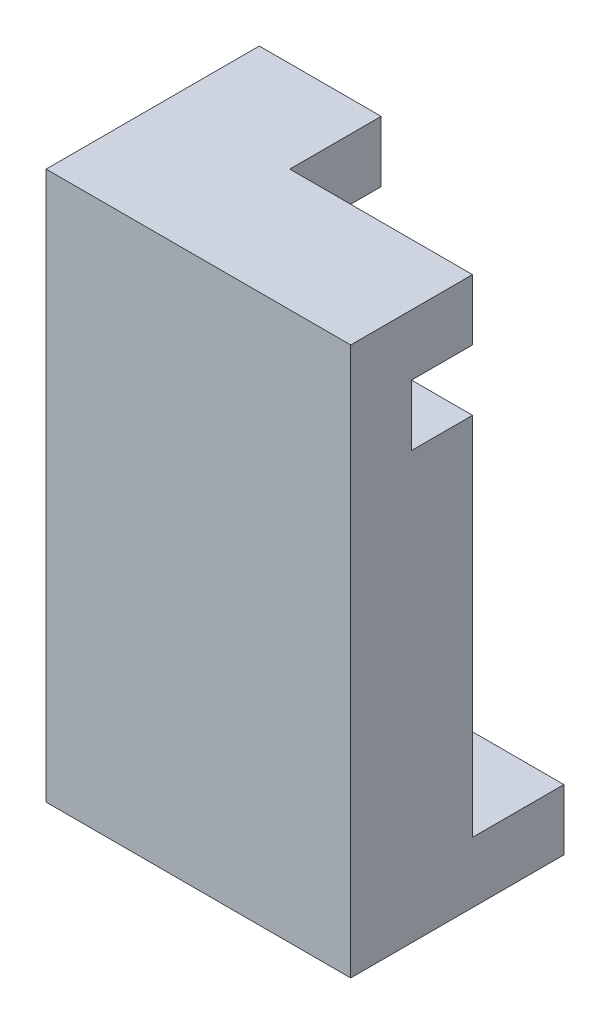
SolidWorks part; units mm, degrees
ref_plane "정면" through (0, 0, 0) normal (0, 0, 1) x (1, 0, 0)
ref_plane "윗면" through (0, 0, 0) normal (0, 1, 0) x (1, 0, 0)
ref_plane "우측면" through (0, 0, 0) normal (1, 0, 0) x (0, 0, -1)
sketch "스케치1" plane through (0, 0, 0) normal (0, 1, 0) x (1, 0, 0)
  line L0 (0, 0) -> (25, 0)
  line L17 (25, 0) -> (25, 10)
  line L18 (25, 10) -> (10, 10)
  line L19 (10, 10) -> (10, 25)
  line L20 (10, 25) -> (0, 25)
  line L21 (0, 25) -> (0, 0)
  dimension "D1" = 10
  dimension "D2" = 10
  dimension "D3" = 25
  dimension "D4" = 25
extrude "보스-돌출1" add sketch "스케치1" along normal blind 40
sketch "스케치2" plane through (0, 0, 0) normal (0, -1, 0) x (1, 0, 0)
  line L0 (25, 0) -> (25, -10) construction
  line L1 (0, 0) -> (25, 0)
  line L2 (0, 0) -> (0, -25)
  line L3 (0, -25) -> (25, -25)
  line L4 (25, 0) -> (25, -25)
  line L5 (10, -25) -> (0, -25) construction
extrude "보스-돌출2" add sketch "스케치2" along normal blind 5
sketch "스케치3" plane through (0, 0, -25) normal (0, 0, -1) x (-1, 0, 0)
  line L0 (-25, 40) -> (-25, 0) construction
  line L1 (-5, 30) -> (-25, 30)
  line L2 (-5, 30) -> (-5, 35)
  line L3 (-5, 35) -> (-25, 35)
  line L4 (-25, 30) -> (-25, 35)
  line L5 (-10, 40) -> (-10, 0) construction
  line L6 (-25, 40) -> (-10, 40) construction
  dimension "D1" = 5
  dimension "D2" = 5
  dimension "D3" = 5
extrude "컷-돌출1" cut sketch "스케치3" against normal blind 20
sketch "스케치4" plane through (10, 0, 0) normal (1, 0, 0) x (0, 0, -1)
  line L0 (10, 40) -> (25, 40) construction
  line L1 (25, -5) -> (17.5, -5)
  line L2 (25, -5) -> (25, 40)
  line L3 (25, 40) -> (17.5, 40)
  line L4 (17.5, -5) -> (17.5, 40)
extrude "컷-돌출2" cut sketch "스케치4" against normal through all both and the other way through all
